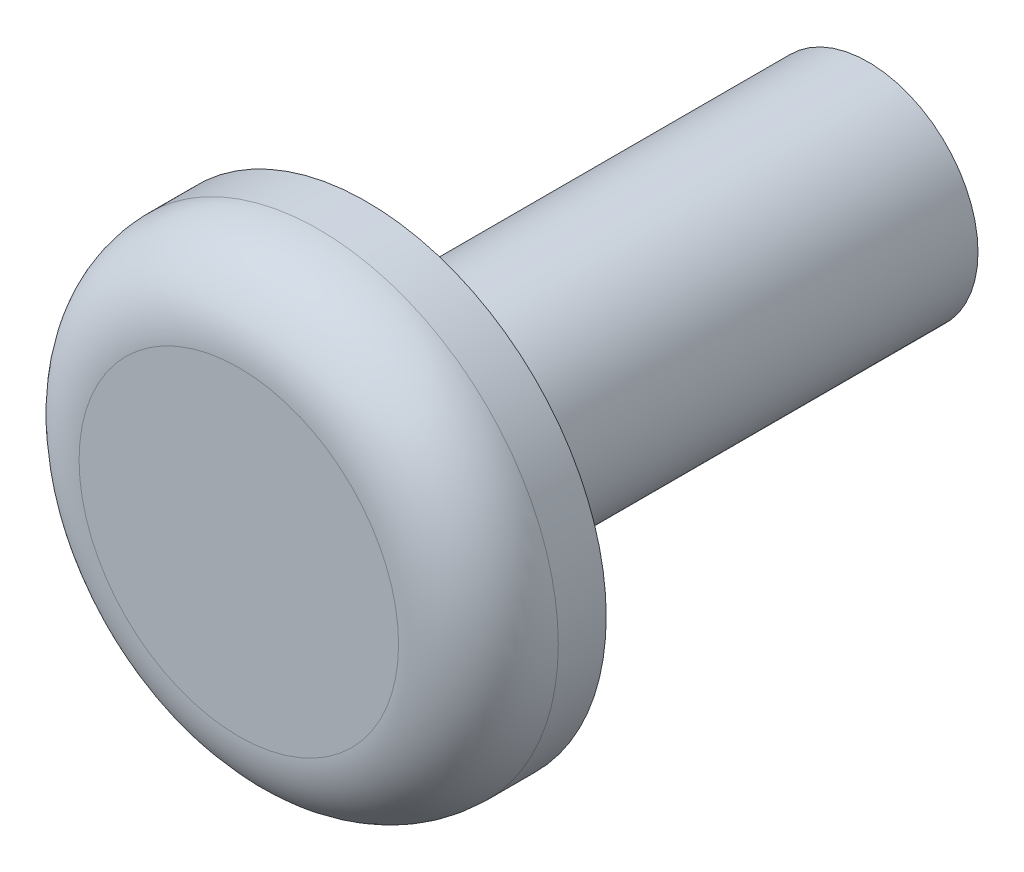
SolidWorks part; units mm, degrees
ref_plane "Front Plane" through (0, 0, 0) normal (0, 0, 1) x (1, 0, 0)
ref_plane "Top Plane" through (0, 0, 0) normal (0, 1, 0) x (1, 0, 0)
ref_plane "Right Plane" through (0, 0, 0) normal (1, 0, 0) x (0, 0, -1)
sketch "Sketch1" plane through (0, 0, 0) normal (0, 0, 1) x (1, 0, 0)
  circle A0 centre (0, 0) radius 3.4375
  dimension "D1" = 6.875
extrude "Boss-Extrude1" add sketch "Sketch1" along normal blind 15.7
sketch "Sketch2" plane through (0, 0, 15.7) normal (0, 0, 1) x (1, 0, 0)
  circle A0 centre (0, 0) radius 7.5
  dimension "D1" = 15
extrude "Boss-Extrude2" add sketch "Sketch2" along normal blind 4
sketch "Sketch3" plane through (0, 0, 0) normal (0, 0, -1) x (-1, 0, 0)
  circle A0 centre (0, 0) radius 1.5
extrude "Cut-Extrude1" cut sketch "Sketch3" against normal blind 5
chamfer "Chamfer1" distance 0.2 distance2 1 1 edges at (-1.5, 0, 0)
fillet "Fillet1" radius 2.5 1 edges at (7.5, 0, 19.7)
